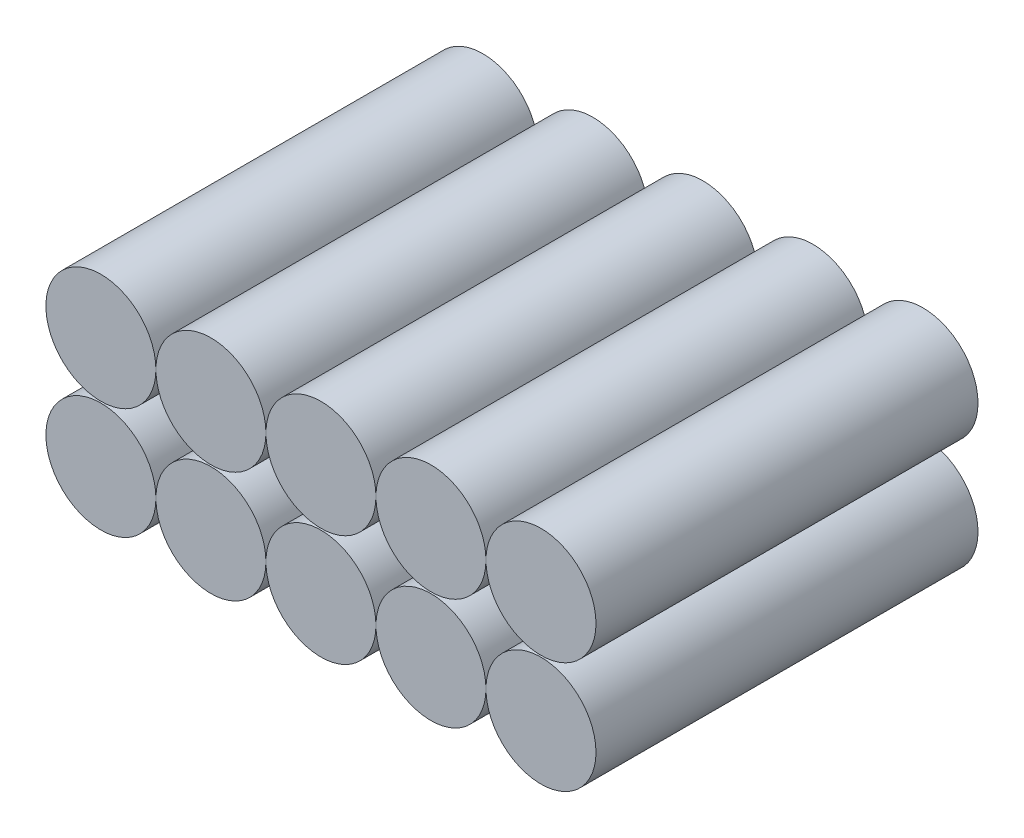
SolidWorks part; units mm, degrees
ref_plane "Front" through (0, 0, 0) normal (0, 0, 1) x (1, 0, 0)
ref_plane "Top" through (0, 0, 0) normal (0, 1, 0) x (1, 0, 0)
ref_plane "Right" through (0, 0, 0) normal (1, 0, 0) x (0, 0, -1)
sketch "Sketch1" plane through (0, 0, 0) normal (0, 0, 1) x (1, 0, 0)
  circle A0 centre (0, 0) radius 7.2
  circle A1 centre (0, 14.6) radius 7.2
  circle A2 centre (14.4, 0) radius 7.2
  circle A3 centre (14.4, 14.6) radius 7.2
  circle A4 centre (28.8, 0) radius 7.2
  circle A5 centre (28.8, 14.6) radius 7.2
  circle A6 centre (43.2, 0) radius 7.2
  circle A7 centre (43.2, 14.6) radius 7.2
  circle A8 centre (57.6, 0) radius 7.2
  circle A9 centre (57.6, 14.6) radius 7.2
  dimension "D1" = 5
  dimension "D2" = 2
extrude "Boss-Extrude1" add sketch "Sketch1" against normal blind 50 contours A0 | A4 | A2 | A6 | A8 | A1 | A3 | A5 | A7 | A9
sketch "Sketch2" plane through (0, 0, 0) normal (1, 0, 0) x (0, 0, -1)
  circle A0 centre (5, 7.3) radius 1.5
  circle A1 centre (8.25, 7.3) radius 1.5
  dimension "D1" = 2
